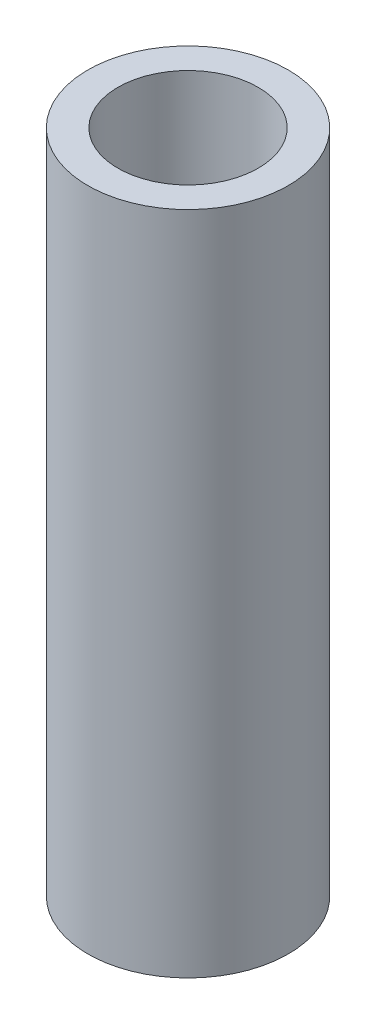
SolidWorks part; units mm, degrees
material "6061 Alloy"
ref_plane "Front Plane" through (0, 0, 0) normal (0, 0, 1) x (1, 0, 0)
ref_plane "Top Plane" through (0, 0, 0) normal (0, 1, 0) x (1, 0, 0)
ref_plane "Right Plane" through (0, 0, 0) normal (1, 0, 0) x (0, 0, -1)
sketch "Sketch1" plane through (0, 0, 0) normal (0, 1, 0) x (1, 0, 0)
  circle A0 centre (0, 0) radius 1.75
  circle A1 centre (0, 0) radius 2.5
  dimension "D1" = 3.5
  dimension "D2" = 5
extrude "Boss-Extrude1" add sketch "Sketch1" along normal mid plane 16.6
